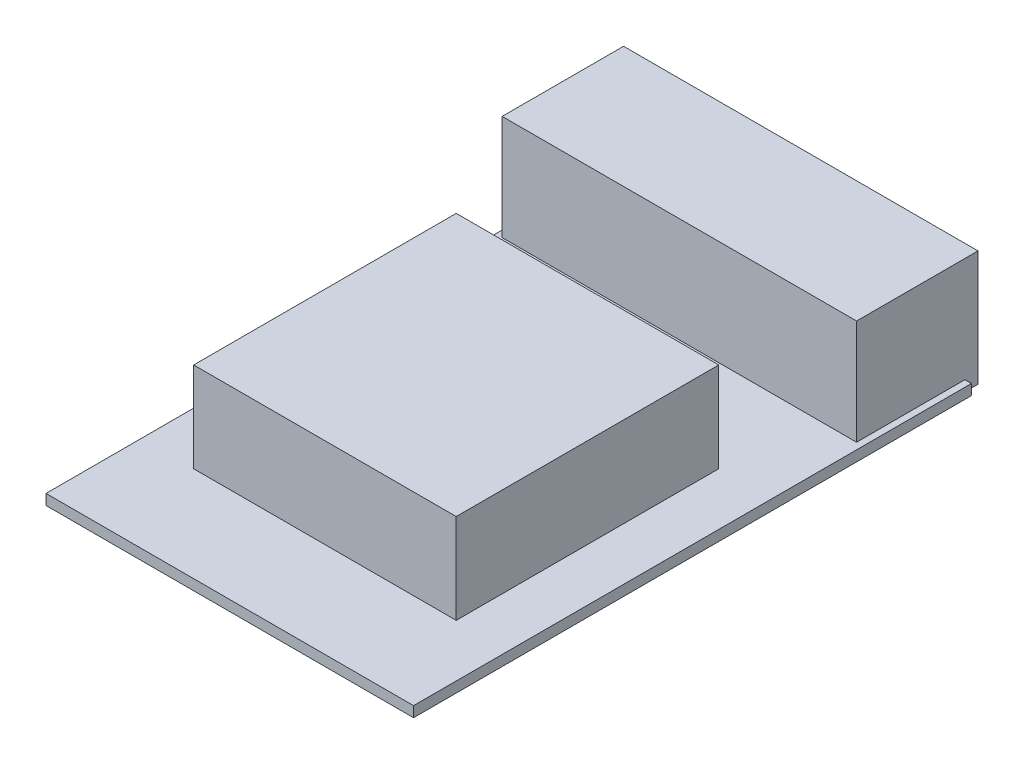
SolidWorks part; units mm, degrees
ref_plane "Front Plane" through (0, 0, 0) normal (0, 0, 1) x (1, 0, 0)
ref_plane "Top Plane" through (0, 0, 0) normal (0, 1, 0) x (1, 0, 0)
ref_plane "Right Plane" through (0, 0, 0) normal (1, 0, 0) x (0, 0, -1)
sketch "Sketch1" plane through (0, 0, 0) normal (0, 1, 0) x (1, 0, 0)
  line L1 (-126, 42.5) -> (-70, 42.5)
  line L2 (-126, 42.5) -> (-126, -42.5)
  line L3 (-126, -42.5) -> (-70, -42.5)
  line L4 (-70, 42.5) -> (-70, -42.5)
extrude "Boss-Extrude1" add sketch "Sketch1" along normal blind 1.6
sketch "Sketch2" plane through (0, 0, 0) normal (0, 1, 0) x (1, 0, 0)
  line L1 (-125, 44.5) -> (-71, 44.5)
  line L2 (-125, 44.5) -> (-125, 26)
  line L3 (-125, 26) -> (-71, 26)
  line L4 (-71, 44.5) -> (-71, 26)
extrude "Boss-Extrude2" add sketch "Sketch2" along normal blind 17.6
sketch "Sketch3" plane through (0, 0, 0) normal (0, 1, 0) x (1, 0, 0)
  line L1 (-118, 12) -> (-78, 12)
  line L2 (-118, 12) -> (-118, -28)
  line L3 (-118, -28) -> (-78, -28)
  line L4 (-78, 12) -> (-78, -28)
extrude "Boss-Extrude3" add sketch "Sketch3" along normal blind 15.3
